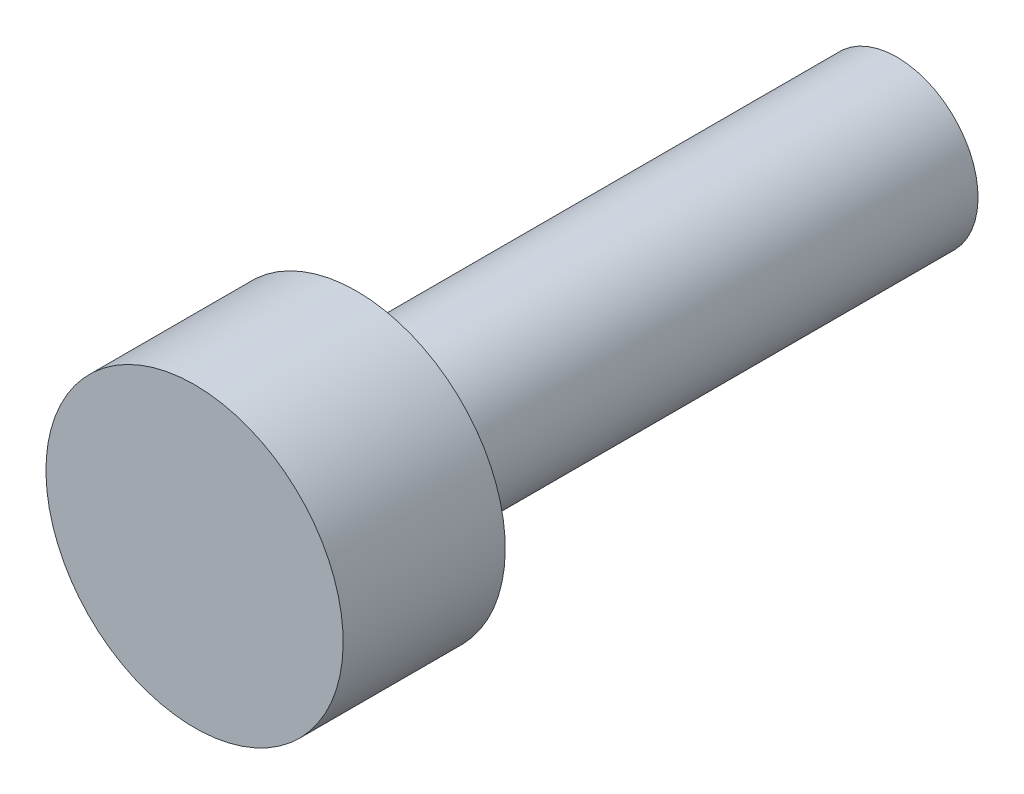
SolidWorks part; units mm, degrees
ref_plane "Front Plane" through (0, 0, 0) normal (0, 0, 1) x (1, 0, 0)
ref_plane "Top Plane" through (0, 0, 0) normal (0, 1, 0) x (1, 0, 0)
ref_plane "Right Plane" through (0, 0, 0) normal (1, 0, 0) x (0, 0, -1)
sketch "Sketch1" plane through (0, 0, 0) normal (1, 0, 0) x (0, 0, -1)
  line L0 (0, 0) -> (0, 2.75)
  line L1 (0, 2.75) -> (3, 2.75)
  line L2 (3, 2.75) -> (3, 1.5)
  line L3 (3, 1.5) -> (13, 1.5)
  line L4 (13, 1.5) -> (13, 0)
  line L5 (13, 0) -> (0, 0) construction
  line L6 (0, 0) -> (13, 0)
  dimension "D1" = 10
  dimension "D2" = 2.75
  dimension "D3" = 1.5
  dimension "D4" = 3
revolve "Revolve1" add sketch "Sketch1" angle 360 about L5
